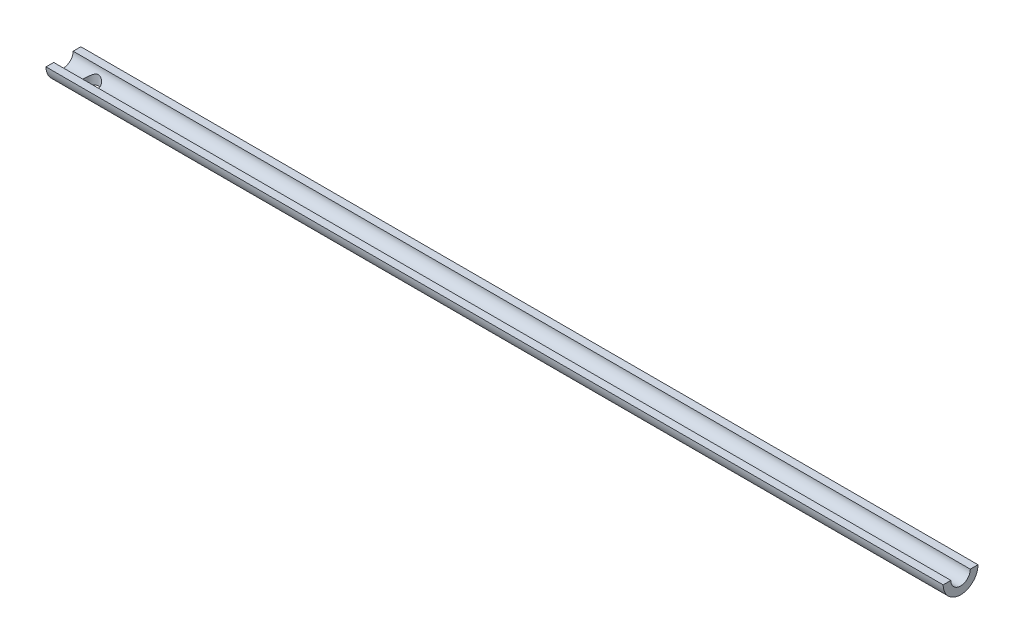
SolidWorks part; units mm, degrees
ref_plane "Front Plane" through (0, 0, 0) normal (0, 0, 1) x (1, 0, 0)
ref_plane "Top Plane" through (0, 0, 0) normal (0, 1, 0) x (1, 0, 0)
ref_plane "Right Plane" through (0, 0, 0) normal (1, 0, 0) x (0, 0, -1)
sketch "Sketch1" plane through (0, 0, 0) normal (0, 1, 0) x (1, 0, 0)
  line L1 (0, 0) -> (735.584, 0)
  line L2 (0, 0) -> (0, 38.1)
  line L3 (0, 38.1) -> (735.584, 38.1)
  line L4 (735.584, 0) -> (735.584, 38.1)
  dimension "blank_length" = 735.584
  dimension "blank_width" = 38.1
extrude "wood block" add sketch "Sketch1" along normal blind 19.05
sketch "Sketch2" plane through (735.584, 0, 0) normal (1, 0, 0) x (0, 0, -1)
  line L0 (0, 19.05) -> (38.1, 19.05) construction
  circle A0 centre (19.05, 19.05) radius 7.9756
  dimension "inner_diameter" = 15.9512
extrude "inner bore" cut sketch "Sketch2" against normal through all
sketch "Sketch3" plane through (0, 0, 0) normal (0, 1, 0) x (1, 0, 0)
  line L0 (0, 19.05) -> (22.225, 19.05) construction
  line L1 (0, 27.0256) -> (0, 11.0744) construction
  circle A0 centre (22.225, 19.05) radius 6.3881
  point P3 (15.8369, 19.05)
  dimension "mouthpiece_diameter" = 12.7762
  dimension "mouthpiece_location" = 22.225
extrude "mouthpiece through hole" cut sketch "Sketch3" along normal through all
sketch "Sketch5" plane through (0, 0, 0) normal (0, -1, 0) x (1, 0, 0)
  circle A0 centre (22.225, -19.05) radius 8.128
  dimension "counterbore_diameter" = 16.256
extrude "counterbore" cut sketch "Sketch5" against normal blind 5.5499
sketch "Sketch4" plane through (0, 0, 0) normal (-1, 0, 0) x (0, 0, 1)
  circle A0 centre (-19.05, 19.05) radius 14.2875
  arc A1 (-27.0256, 19.05) -> (-11.0744, 19.05) centre (-19.05, 19.05) ccw construction
  dimension "outer_diameter" = 28.575
extrude "outer diameter" cut sketch "Sketch4" against normal through all flip side to cut
equation "\"g_mp_block_OD\"= 28.575mm"
equation "\"g_mp_block_ID\"= 15.875mm"
equation "\"g_mp_block_L_blank\"= 735.584mm"
equation "\"g_mp_block_blank_W\"= 38.1mm"
equation "\"g_mp_tube_OD\"= 15.875mm"
equation "\"g_thru_passage_OD\"= 12.7mm"
equation "\"c_glue_gap\"= 0.0762mm"
equation "\"c_slip_fit\"= 0.381mm"
equation "\"thickness@wood block\"= \"g_mp_block_blank_W\" / 2"
equation "\"blank_length@Sketch1\"= \"g_mp_block_L_blank\""
equation "\"blank_width@Sketch1\"= \"g_mp_block_blank_W\""
equation "\"outer_diameter@Sketch4\"= \"g_mp_block_OD\""
equation "\"inner_diameter@Sketch2\"= \"g_mp_block_ID\" + \"c_glue_gap\""
equation "\"mouthpiece_diameter@Sketch3\"= \"g_thru_passage_OD\" + \"c_glue_gap\""
equation "\"counterbore_diameter@Sketch5\"= \"g_mp_tube_OD\" + \"c_slip_fit\""
